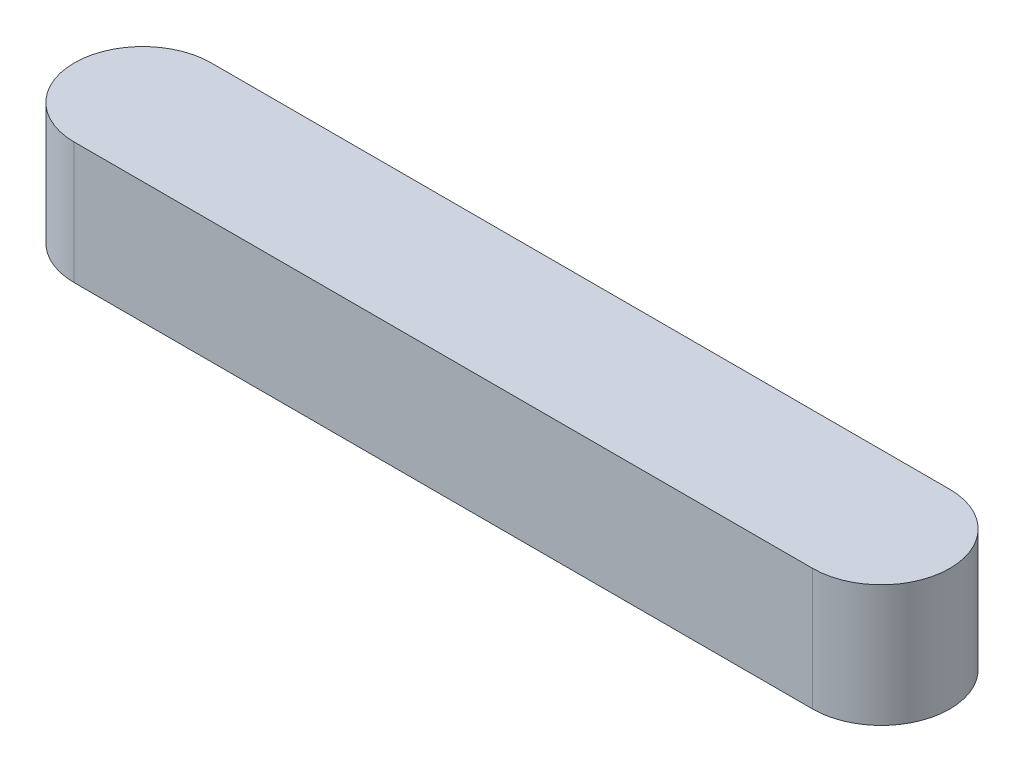
SolidWorks part; units mm, degrees
material "Cast Alloy Steel"
ref_plane "Front Plane" through (0, 0, 0) normal (0, 0, 1) x (1, 0, 0)
ref_plane "Top Plane" through (0, 0, 0) normal (0, 1, 0) x (1, 0, 0)
ref_plane "Right Plane" through (0, 0, 0) normal (1, 0, 0) x (0, 0, -1)
sketch "Sketch1" plane through (0, 0, 0) normal (0, 1, 0) x (1, 0, 0)
  line L0 (-57.5, 0) -> (57.5, 0) construction
  line L1 (-48.5, 0) -> (48.5, 0) construction
  line L2 (-48.5, 9) -> (48.5, 9)
  line L3 (-48.5, -9) -> (48.5, -9)
  arc A0 (-48.5, 9) -> (-48.5, -9) centre (-48.5, 0) ccw
  arc A1 (48.5, -9) -> (48.5, 9) centre (48.5, 0) ccw
  point P4 (0, 0)
  point P7 (0, 0)
  dimension "D" = 9
  dimension "L" = 115
extrude "Boss-Extrude1" add sketch "Sketch1" along normal blind 16
sketch "Sketch2" plane through (0, 16, 0) normal (0, 1, 0) x (1, 0, 0)
  line L0 (48.5, 9) -> (-48.5, 9) construction
  line L1 (0, 9) -> (57.5, 9)
  line L2 (0, 9) -> (0, -9)
  line L3 (0, -9) -> (57.5, -9)
  line L4 (57.5, 9) -> (57.5, -9)
  line L5 (-48.5, -9) -> (48.5, -9) construction
  arc A0 (48.5, -9) -> (48.5, 9) centre (48.5, 0) ccw construction
extrude "Cut-Extrude1" [suppressed] cut sketch "Sketch2" against normal through all
equation "\"L\"= 115"
equation "\"D\"= 9"
equation "\"H\"= 16"
equation "\"Cut-Extrude1\"= IIF ( \"L\" = 160 , \"unsuppressed\" , IIF ( \"L\" = 100 , \"unsuppressed\" , \"suppressed\" ) )"
equation "\"L@Sketch1\"=\"L\""
equation "\"D@Sketch1\"=\"D\""
equation "\"H@Boss-Extrude1\"=\"H\""
